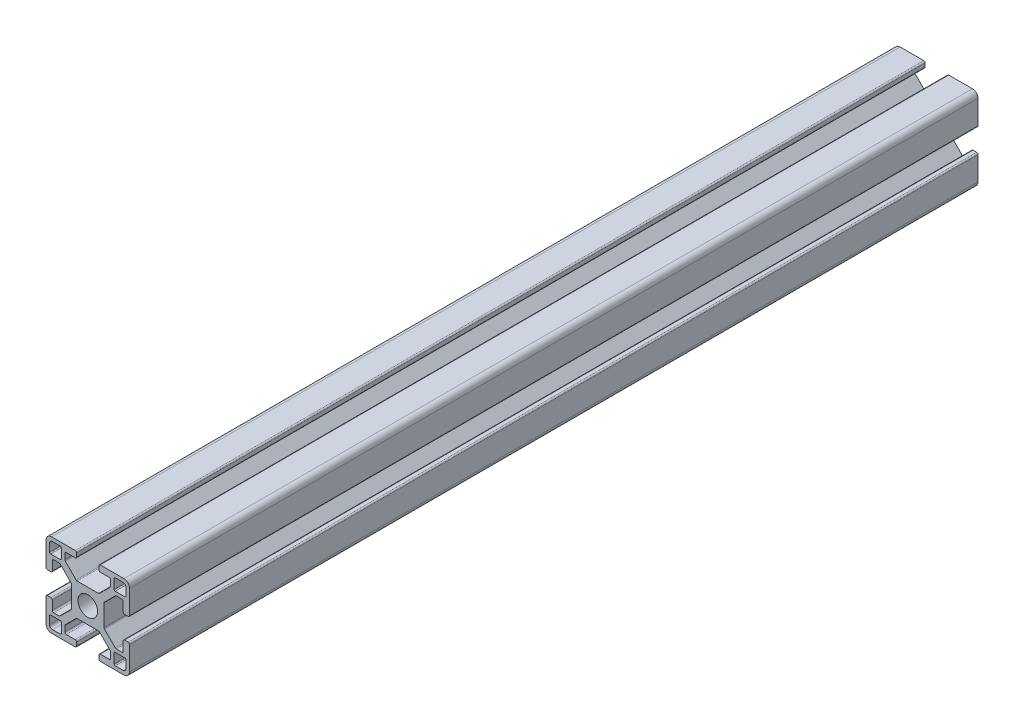
SolidWorks part; units mm, degrees
ref_plane "Front Plane" through (0, 0, 0) normal (0, 0, 1) x (1, 0, 0)
ref_plane "Top Plane" through (0, 0, 0) normal (0, 1, 0) x (1, 0, 0)
ref_plane "Right Plane" through (0, 0, 0) normal (1, 0, 0) x (0, 0, -1)
sketch "Sketch1" plane through (0, 0, 0) normal (0, 0, 1) x (1, 0, 0)
  line L0 (3.9799, -2.4733) -> (3.1981, -1.4942) construction
  line L1 (1.4942, -3.1981) -> (2.4733, -3.9799) construction
  line L2 (-2.4733, -3.9799) -> (-1.4942, -3.1981) construction
  line L3 (-3.1981, -1.4942) -> (-3.9799, -2.4733) construction
  line L4 (-3.9799, 2.4733) -> (-3.1981, 1.4942) construction
  line L5 (-1.4942, 3.1981) -> (-2.4733, 3.9799) construction
  line L6 (2.4733, 3.9799) -> (1.4942, 3.1981) construction
  line L7 (3.1981, 1.4942) -> (3.9799, 2.4733) construction
  line L8 (-12.6999, -13.6999) -> (-9.881, -13.6999)
  line L9 (-13.6999, -9.881) -> (-13.6999, -12.6999)
  line L10 (-9.88, -9.5) -> (-13.3189, -9.5)
  line L11 (-9.5, -13.3189) -> (-9.5, -9.88)
  line L12 (13.6999, -12.6999) -> (13.6999, -9.881)
  line L13 (9.881, -13.6999) -> (12.6999, -13.6999)
  line L14 (9.5, -9.88) -> (9.5, -13.3189)
  line L15 (13.3189, -9.5) -> (9.88, -9.5)
  line L16 (9.88, 9.5) -> (13.3189, 9.5)
  line L17 (9.5, 13.3189) -> (9.5, 9.88)
  line L18 (12.6999, 13.6999) -> (9.881, 13.6999)
  line L19 (13.6999, 9.881) -> (13.6999, 12.6999)
  line L20 (-13.6999, 12.6999) -> (-13.6999, 9.881)
  line L21 (-9.881, 13.6999) -> (-12.6999, 13.6999)
  line L22 (-9.5, 9.88) -> (-9.5, 13.3189)
  line L23 (-13.3189, 9.5) -> (-9.88, 9.5)
  line L24 (14.4999, -4) -> (13.2425, -4)
  line L25 (12.7425, -4.5) -> (12.7425, -7.7325)
  line L26 (12.2428, -8.25) -> (10.2602, -8.25)
  line L27 (9.9066, -8.1035) -> (5.9811, -4.178)
  line L28 (5.8347, -3.8245) -> (5.8347, -1.0125)
  line L29 (5.8347, -1.0125) -> (5.3247, -0.0625) construction
  line L30 (5.3247, -0.0625) -> (5.8347, 0.8875) construction
  line L31 (5.8347, 0.8875) -> (5.8347, 3.8245)
  line L32 (5.9811, 4.178) -> (9.9066, 8.1035)
  line L33 (10.2602, 8.25) -> (12.2428, 8.25)
  line L34 (12.7425, 7.7325) -> (12.7425, 4.5)
  line L35 (13.2425, 4) -> (14.4999, 4)
  line L36 (14.9999, 4.5) -> (14.9999, 12.9999)
  line L37 (12.9999, 14.9999) -> (4.5, 14.9999)
  line L38 (4, 14.4999) -> (4, 13.2425)
  line L39 (4.5, 12.7425) -> (7.7325, 12.7425)
  line L40 (8.25, 12.2428) -> (8.25, 10.2602)
  line L41 (8.1035, 9.9066) -> (4.178, 5.9811)
  line L42 (3.8245, 5.8347) -> (0.95, 5.8347)
  line L43 (0.95, 5.8347) -> (0, 5.3247) construction
  line L44 (0, 5.3247) -> (-0.95, 5.8347) construction
  line L45 (-0.95, 5.8347) -> (-3.8245, 5.8347)
  line L46 (-4.178, 5.9811) -> (-8.1035, 9.9066)
  line L47 (-8.25, 10.2602) -> (-8.25, 12.2428)
  line L48 (-7.7325, 12.7425) -> (-4.5, 12.7425)
  line L49 (-4, 13.2425) -> (-4, 14.4999)
  line L50 (-4.5, 14.9999) -> (-12.9999, 14.9999)
  line L51 (-14.9999, 12.9999) -> (-14.9999, 4.5)
  line L52 (-14.4999, 4) -> (-13.2425, 4)
  line L53 (-12.7425, 4.5) -> (-12.7425, 7.7325)
  line L54 (-12.2428, 8.25) -> (-10.2602, 8.25)
  line L55 (-9.9066, 8.1035) -> (-5.9811, 4.178)
  line L56 (-5.8347, 3.8245) -> (-5.8347, 0.8875)
  line L57 (-5.8347, 0.8875) -> (-5.3247, -0.0625) construction
  line L58 (-5.3247, -0.0625) -> (-5.8347, -1.0125) construction
  line L59 (-5.8347, -1.0125) -> (-5.8347, -3.8245)
  line L60 (-5.9811, -4.178) -> (-9.9066, -8.1035)
  line L61 (-10.2602, -8.25) -> (-12.2428, -8.25)
  line L62 (-12.7425, -7.7325) -> (-12.7425, -4.5)
  line L63 (-13.2425, -4) -> (-14.4999, -4)
  line L64 (-14.9999, -4.5) -> (-14.9999, -12.9999)
  line L65 (-12.9999, -14.9999) -> (-4.5, -14.9999)
  line L66 (-4, -14.4999) -> (-4, -13.2425)
  line L67 (-4.5, -12.7425) -> (-7.7325, -12.7425)
  line L68 (-8.25, -12.2428) -> (-8.25, -10.2602)
  line L69 (-8.1035, -9.9066) -> (-4.178, -5.9811)
  line L70 (-3.8245, -5.8347) -> (-0.95, -5.8347)
  line L71 (-0.95, -5.8347) -> (0, -5.3247) construction
  line L72 (0, -5.3247) -> (0.95, -5.8347) construction
  line L73 (0.95, -5.8347) -> (3.8245, -5.8347)
  line L74 (4.178, -5.9811) -> (8.1035, -9.9066)
  line L75 (8.25, -10.2602) -> (8.25, -12.2428)
  line L76 (7.7325, -12.7425) -> (4.5, -12.7425)
  line L77 (4, -13.2425) -> (4, -14.4999)
  line L78 (4.5, -14.9999) -> (12.9999, -14.9999)
  line L79 (14.9999, -12.9999) -> (14.9999, -4.5)
  line L80 (-5.8347, -1.0125) -> (-5.8347, 0.8875)
  line L81 (-0.95, 5.8347) -> (0.95, 5.8347)
  line L82 (5.8347, 0.8875) -> (5.8347, -1.0125)
  line L83 (-0.95, -5.8347) -> (0.95, -5.8347)
  arc A0 (2.4733, -3.9799) -> (3.9799, -2.4733) centre (3.1422, -3.1422) ccw construction
  arc A1 (-1.4942, -3.1981) -> (1.4942, -3.1981) centre (0, 0) ccw construction
  arc A2 (-3.9799, -2.4733) -> (-2.4733, -3.9799) centre (-3.1422, -3.1422) ccw construction
  arc A3 (-3.1981, 1.4942) -> (-3.1981, -1.4942) centre (0, 0) ccw construction
  arc A4 (-2.4733, 3.9799) -> (-3.9799, 2.4733) centre (-3.1422, 3.1422) ccw construction
  arc A5 (1.4942, 3.1981) -> (-1.4942, 3.1981) centre (0, 0) ccw construction
  arc A6 (3.9799, 2.4733) -> (2.4733, 3.9799) centre (3.1422, 3.1422) ccw construction
  arc A7 (3.1981, -1.4942) -> (3.1981, 1.4942) centre (0, 0) ccw construction
  arc A8 (-13.6999, -12.6999) -> (-12.6999, -13.6999) centre (-12.6999, -12.6999) ccw
  arc A9 (-13.3189, -9.5) -> (-13.6999, -9.881) centre (-13.3189, -9.881) ccw
  arc A10 (-9.5, -9.88) -> (-9.88, -9.5) centre (-9.88, -9.88) ccw
  arc A11 (-9.881, -13.6999) -> (-9.5, -13.3189) centre (-9.881, -13.3189) ccw
  arc A12 (12.6999, -13.6999) -> (13.6999, -12.6999) centre (12.6999, -12.6999) ccw
  arc A13 (9.5, -13.3189) -> (9.881, -13.6999) centre (9.881, -13.3189) ccw
  arc A14 (9.88, -9.5) -> (9.5, -9.88) centre (9.88, -9.88) ccw
  arc A15 (13.6999, -9.881) -> (13.3189, -9.5) centre (13.3189, -9.881) ccw
  arc A16 (9.5, 9.88) -> (9.88, 9.5) centre (9.88, 9.88) ccw
  arc A17 (9.881, 13.6999) -> (9.5, 13.3189) centre (9.881, 13.3189) ccw
  arc A18 (13.6999, 12.6999) -> (12.6999, 13.6999) centre (12.6999, 12.6999) ccw
  arc A19 (13.3189, 9.5) -> (13.6999, 9.881) centre (13.3189, 9.881) ccw
  arc A20 (14.9999, -4.5) -> (14.4999, -4) centre (14.4999, -4.5) ccw
  arc A21 (13.2425, -4) -> (12.7425, -4.5) centre (13.2425, -4.5) ccw
  arc A22 (12.2428, -8.25) -> (12.7425, -7.7325) centre (12.2428, -7.75) ccw
  arc A23 (9.9066, -8.1035) -> (10.2602, -8.25) centre (10.2602, -7.75) ccw
  arc A24 (5.8347, -3.8245) -> (5.9811, -4.178) centre (6.3347, -3.8245) ccw
  arc A25 (5.9811, 4.178) -> (5.8347, 3.8245) centre (6.3347, 3.8245) ccw
  arc A26 (10.2602, 8.25) -> (9.9066, 8.1035) centre (10.2602, 7.75) ccw
  arc A27 (12.7425, 7.7325) -> (12.2428, 8.25) centre (12.2428, 7.75) ccw
  arc A28 (12.7425, 4.5) -> (13.2425, 4) centre (13.2425, 4.5) ccw
  arc A29 (14.4999, 4) -> (14.9999, 4.5) centre (14.4999, 4.5) ccw
  arc A30 (14.9999, 12.9999) -> (12.9999, 14.9999) centre (12.9999, 12.9999) ccw
  arc A31 (4.5, 14.9999) -> (4, 14.4999) centre (4.5, 14.4999) ccw
  arc A32 (4, 13.2425) -> (4.5, 12.7425) centre (4.5, 13.2425) ccw
  arc A33 (8.25, 12.2428) -> (7.7325, 12.7425) centre (7.75, 12.2428) ccw
  arc A34 (8.1035, 9.9066) -> (8.25, 10.2602) centre (7.75, 10.2602) ccw
  arc A35 (3.8245, 5.8347) -> (4.178, 5.9811) centre (3.8245, 6.3347) ccw
  arc A36 (-4.178, 5.9811) -> (-3.8245, 5.8347) centre (-3.8245, 6.3347) ccw
  arc A37 (-8.25, 10.2602) -> (-8.1035, 9.9066) centre (-7.75, 10.2602) ccw
  arc A38 (-7.7325, 12.7425) -> (-8.25, 12.2428) centre (-7.75, 12.2428) ccw
  arc A39 (-4.5, 12.7425) -> (-4, 13.2425) centre (-4.5, 13.2425) ccw
  arc A40 (-4, 14.4999) -> (-4.5, 14.9999) centre (-4.5, 14.4999) ccw
  arc A41 (-12.9999, 14.9999) -> (-14.9999, 12.9999) centre (-12.9999, 12.9999) ccw
  arc A42 (-14.9999, 4.5) -> (-14.4999, 4) centre (-14.4999, 4.5) ccw
  arc A43 (-13.2425, 4) -> (-12.7425, 4.5) centre (-13.2425, 4.5) ccw
  arc A44 (-12.2428, 8.25) -> (-12.7425, 7.7325) centre (-12.2428, 7.75) ccw
  arc A45 (-9.9066, 8.1035) -> (-10.2602, 8.25) centre (-10.2602, 7.75) ccw
  arc A46 (-5.8347, 3.8245) -> (-5.9811, 4.178) centre (-6.3347, 3.8245) ccw
  arc A47 (-5.9811, -4.178) -> (-5.8347, -3.8245) centre (-6.3347, -3.8245) ccw
  arc A48 (-10.2602, -8.25) -> (-9.9066, -8.1035) centre (-10.2602, -7.75) ccw
  arc A49 (-12.7425, -7.7325) -> (-12.2428, -8.25) centre (-12.2428, -7.75) ccw
  arc A50 (-12.7425, -4.5) -> (-13.2425, -4) centre (-13.2425, -4.5) ccw
  arc A51 (-14.4999, -4) -> (-14.9999, -4.5) centre (-14.4999, -4.5) ccw
  arc A52 (-14.9999, -12.9999) -> (-12.9999, -14.9999) centre (-12.9999, -12.9999) ccw
  arc A53 (-4.5, -14.9999) -> (-4, -14.4999) centre (-4.5, -14.4999) ccw
  arc A54 (-4, -13.2425) -> (-4.5, -12.7425) centre (-4.5, -13.2425) ccw
  arc A55 (-8.25, -12.2428) -> (-7.7325, -12.7425) centre (-7.75, -12.2428) ccw
  arc A56 (-8.1035, -9.9066) -> (-8.25, -10.2602) centre (-7.75, -10.2602) ccw
  arc A57 (-3.8245, -5.8347) -> (-4.178, -5.9811) centre (-3.8245, -6.3347) ccw
  arc A58 (4.178, -5.9811) -> (3.8245, -5.8347) centre (3.8245, -6.3347) ccw
  arc A59 (8.25, -10.2602) -> (8.1035, -9.9066) centre (7.75, -10.2602) ccw
  arc A60 (7.7325, -12.7425) -> (8.25, -12.2428) centre (7.75, -12.2428) ccw
  arc A61 (4.5, -12.7425) -> (4, -13.2425) centre (4.5, -13.2425) ccw
  arc A62 (4, -14.4999) -> (4.5, -14.9999) centre (4.5, -14.4999) ccw
  arc A63 (12.9999, -14.9999) -> (14.9999, -12.9999) centre (12.9999, -12.9999) ccw
  arc A64 (-12.6999, 13.6999) -> (-13.6999, 12.6999) centre (-12.6999, 12.6999) ccw
  arc A65 (-9.5, 13.3189) -> (-9.881, 13.6999) centre (-9.881, 13.3189) ccw
  arc A66 (-9.88, 9.5) -> (-9.5, 9.88) centre (-9.88, 9.88) ccw
  arc A67 (-13.6999, 9.881) -> (-13.3189, 9.5) centre (-13.3189, 9.881) ccw
  circle A68 centre (0, 0) radius 3.53
extrude "Boss-Extrude1" add sketch "Sketch1" along normal mid plane 304.8
sketch "Sketch2" plane through (0, 0, 152.4) normal (0, 0, 1) x (1, 0, 0)
  line L0 (12.9999, 14.9999) -> (4.5, 14.9999) construction
  line L1 (-4.5, 14.9999) -> (-12.9999, 14.9999) construction
  line L2 (4, 14.4999) -> (4, 13.2425) construction
  line L3 (4.5, 12.7425) -> (7.7325, 12.7425) construction
  line L4 (8.1035, 9.9066) -> (4.178, 5.9811) construction
  line L5 (3.8245, 5.8347) -> (-3.8245, 5.8347) construction
  line L6 (-4.178, 5.9811) -> (-8.1035, 9.9066) construction
  line L7 (-8.25, 10.2602) -> (-8.25, 12.2428) construction
  line L8 (-7.7325, 12.7425) -> (-4.5, 12.7425) construction
  line L9 (-4, 13.2425) -> (-4, 14.4999) construction
  line L10 (12.9999, 14.9999) -> (4.5, 14.9999)
  line L11 (-4.5, 14.9999) -> (-12.9999, 14.9999)
  line L12 (4, 14.4999) -> (4, 13.2425)
  line L13 (4.5, 12.7425) -> (7.7325, 12.7425)
  line L14 (8.1035, 9.9066) -> (4.178, 5.9811)
  line L15 (3.8245, 5.8347) -> (-3.8245, 5.8347)
  line L16 (-4.178, 5.9811) -> (-8.1035, 9.9066)
  line L17 (-8.25, 10.2602) -> (-8.25, 12.2428)
  line L18 (-7.7325, 12.7425) -> (-4.5, 12.7425)
  line L19 (-4, 13.2425) -> (-4, 14.4999)
  arc A0 (14.9999, 12.9999) -> (12.9999, 14.9999) centre (12.9999, 12.9999) ccw construction
  arc A1 (-12.9999, 14.9999) -> (-14.9999, 12.9999) centre (-12.9999, 12.9999) ccw construction
  arc A2 (4.5, 14.9999) -> (4, 14.4999) centre (4.5, 14.4999) ccw construction
  arc A3 (4, 13.2425) -> (4.5, 12.7425) centre (4.5, 13.2425) ccw construction
  arc A4 (8.25, 12.2428) -> (7.7325, 12.7425) centre (7.75, 12.2428) ccw construction
  arc A5 (8.1035, 9.9066) -> (8.25, 10.2602) centre (7.75, 10.2602) ccw construction
  arc A6 (3.8245, 5.8347) -> (4.178, 5.9811) centre (3.8245, 6.3347) ccw construction
  arc A7 (-4.178, 5.9811) -> (-3.8245, 5.8347) centre (-3.8245, 6.3347) ccw construction
  arc A8 (-8.25, 10.2602) -> (-8.1035, 9.9066) centre (-7.75, 10.2602) ccw construction
  arc A9 (-7.7325, 12.7425) -> (-8.25, 12.2428) centre (-7.75, 12.2428) ccw construction
  arc A10 (-4.5, 12.7425) -> (-4, 13.2425) centre (-4.5, 13.2425) ccw construction
  arc A11 (-4, 14.4999) -> (-4.5, 14.9999) centre (-4.5, 14.4999) ccw construction
  arc A12 (14.9999, 12.9999) -> (12.9999, 14.9999) centre (12.9999, 12.9999) ccw
  arc A13 (-12.9999, 14.9999) -> (-14.9999, 12.9999) centre (-12.9999, 12.9999) ccw
  arc A14 (4.5, 14.9999) -> (4, 14.4999) centre (4.5, 14.4999) ccw
  arc A15 (4, 13.2425) -> (4.5, 12.7425) centre (4.5, 13.2425) ccw
  arc A16 (8.25, 12.2428) -> (7.7325, 12.7425) centre (7.75, 12.2428) ccw
  arc A17 (8.1035, 9.9066) -> (8.25, 10.2602) centre (7.75, 10.2602) ccw
  arc A18 (3.8245, 5.8347) -> (4.178, 5.9811) centre (3.8245, 6.3347) ccw
  arc A19 (-4.178, 5.9811) -> (-3.8245, 5.8347) centre (-3.8245, 6.3347) ccw
  arc A20 (-8.25, 10.2602) -> (-8.1035, 9.9066) centre (-7.75, 10.2602) ccw
  arc A21 (-7.7325, 12.7425) -> (-8.25, 12.2428) centre (-7.75, 12.2428) ccw
  arc A22 (-4.5, 12.7425) -> (-4, 13.2425) centre (-4.5, 13.2425) ccw
  arc A23 (-4, 14.4999) -> (-4.5, 14.9999) centre (-4.5, 14.4999) ccw
